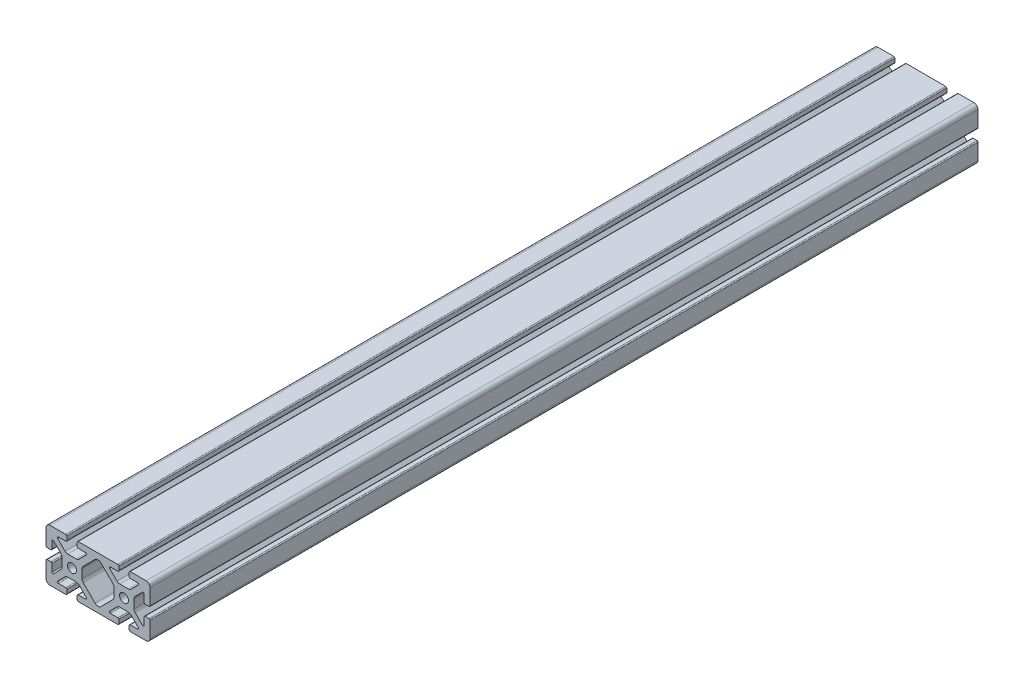
SolidWorks part; units mm, degrees
ref_plane "Front Plane" through (0, 0, 0) normal (0, 0, 1) x (1, 0, 0)
ref_plane "Top Plane" through (0, 0, 0) normal (0, 1, 0) x (1, 0, 0)
ref_plane "Right Plane" through (0, 0, 0) normal (1, 0, 0) x (0, 0, -1)
sketch "Sketch1" plane through (0, 0, 0) normal (0, 0, 1) x (1, 0, 0)
  line L0 (0, 19.939) -> (0, -19.939) construction
  line L1 (-19.939, 0) -> (19.939, 0) construction
  line L2 (-19.939, 16.891) -> (-19.939, 4.7625)
  line L3 (-16.891, 19.939) -> (-4.7625, 19.939)
  line L4 (-4.0005, 19.177) -> (-4.0005, 16.2052)
  line L5 (-4.7625, 15.4432) -> (-10.4246, 15.4432)
  line L6 (-10.9634, 14.1424) -> (-5.395, 8.5741)
  line L7 (-14.1424, 10.9634) -> (-8.5741, 5.395)
  line L8 (-15.4432, 10.4246) -> (-15.4432, 4.7625)
  line L9 (-16.2052, 4.0005) -> (-19.177, 4.0005)
  line L10 (0, 0) -> (-19.939, 19.939) construction
  line L11 (-3.2757, 7.6962) -> (3.2757, 7.6962)
  line L12 (-7.6962, 3.2757) -> (-7.6962, -3.2757)
  line L16 (35.1155, 19.939) -> (4.7625, 19.939)
  line L17 (4.0005, 19.177) -> (4.0005, 16.2052)
  line L18 (4.7625, 15.4432) -> (10.4246, 15.4432)
  line L19 (7.6962, 3.2757) -> (7.6962, -3.2757)
  line L20 (10.9634, 14.1424) -> (5.395, 8.5741)
  line L21 (17.6911, 14.5121) -> (8.5741, 5.395)
  line L22 (-16.2052, -4.0005) -> (-19.177, -4.0005)
  line L23 (-15.4432, -10.4246) -> (-15.4432, -4.7625)
  line L24 (-14.1424, -10.9634) -> (-8.5741, -5.395)
  line L25 (-10.9634, -14.1424) -> (-5.395, -8.5741)
  line L26 (-4.7625, -15.4432) -> (-10.4246, -15.4432)
  line L27 (-4.0005, -19.177) -> (-4.0005, -16.2052)
  line L28 (-16.891, -19.939) -> (-4.7625, -19.939)
  line L29 (-19.939, -16.891) -> (-19.939, -4.7625)
  line L31 (19.939, -19.939) -> (4.7625, -19.939)
  line L32 (4.0005, -19.177) -> (4.0005, -16.2052)
  line L33 (4.7625, -15.4432) -> (10.4246, -15.4432)
  line L34 (10.9634, -14.1424) -> (5.395, -8.5741)
  line L35 (17.6911, -14.5121) -> (8.5741, -5.395)
  line L38 (-3.2757, -7.6962) -> (3.2757, -7.6962)
  line L39 (19.939, 0) -> (19.939, -19.939) construction
  line L40 (43.1537, -7.6962) -> (36.6023, -7.6962)
  line L43 (22.1869, -14.5121) -> (31.3039, -5.395)
  line L44 (28.9146, -14.1424) -> (34.483, -8.5741)
  line L45 (35.1155, -15.4432) -> (29.4534, -15.4432)
  line L46 (35.8775, -19.177) -> (35.8775, -16.2052)
  line L47 (19.939, -19.939) -> (35.1155, -19.939)
  line L48 (59.817, -16.891) -> (59.817, -4.7625)
  line L49 (56.769, -19.939) -> (44.6405, -19.939)
  line L50 (43.8785, -19.177) -> (43.8785, -16.2052)
  line L51 (44.6405, -15.4432) -> (50.3026, -15.4432)
  line L52 (50.8414, -14.1424) -> (45.273, -8.5741)
  line L53 (54.0204, -10.9634) -> (48.4521, -5.395)
  line L54 (55.3212, -10.4246) -> (55.3212, -4.7625)
  line L55 (56.0832, -4.0005) -> (59.055, -4.0005)
  line L56 (22.1869, 14.5121) -> (31.3039, 5.395)
  line L57 (28.9146, 14.1424) -> (34.483, 8.5741)
  line L58 (32.1818, 3.2757) -> (32.1818, -3.2757)
  line L59 (35.1155, 15.4432) -> (29.4534, 15.4432)
  line L60 (35.8775, 19.177) -> (35.8775, 16.2052)
  line L64 (47.5742, 3.2757) -> (47.5742, -3.2757)
  line L65 (43.1537, 7.6962) -> (36.6023, 7.6962)
  line L66 (56.0832, 4.0005) -> (59.055, 4.0005)
  line L67 (55.3212, 10.4246) -> (55.3212, 4.7625)
  line L68 (54.0204, 10.9634) -> (48.4521, 5.395)
  line L69 (50.8414, 14.1424) -> (45.273, 8.5741)
  line L70 (44.6405, 15.4432) -> (50.3026, 15.4432)
  line L71 (43.8785, 19.177) -> (43.8785, 16.2052)
  line L72 (56.769, 19.939) -> (44.6405, 19.939)
  line L73 (59.817, 16.891) -> (59.817, 4.7625)
  circle A0 centre (0, 0) radius 3.4036
  arc A1 (-19.939, 16.891) -> (-16.891, 19.939) centre (-16.891, 16.891) cw
  arc A2 (-14.1424, 10.9634) -> (-15.4432, 10.4246) centre (-14.6812, 10.4246) ccw
  arc A3 (-10.4246, 15.4432) -> (-10.9634, 14.1424) centre (-10.4246, 14.6812) ccw
  arc A4 (-4.7625, 19.939) -> (-4.0005, 19.177) centre (-4.7625, 19.177) cw
  arc A5 (-19.939, 4.7625) -> (-19.177, 4.0005) centre (-19.177, 4.7625) ccw
  arc A6 (-15.4432, 4.7625) -> (-16.2052, 4.0005) centre (-16.2052, 4.7625) cw
  arc A7 (-4.0005, 16.2052) -> (-4.7625, 15.4432) centre (-4.7625, 16.2052) cw
  arc A8 (-3.2757, 7.6962) -> (-5.395, 8.5741) centre (-3.2757, 10.6934) cw
  arc A9 (-7.6962, 3.2757) -> (-8.5741, 5.395) centre (-10.6934, 3.2757) ccw
  arc A10 (22.1869, 14.5121) -> (17.6911, 14.5121) centre (19.939, 12.2642) ccw
  arc A11 (17.6911, -14.5121) -> (22.1869, -14.5121) centre (19.939, -12.2642) ccw
  arc A13 (4.7625, 19.939) -> (4.0005, 19.177) centre (4.7625, 19.177) ccw
  arc A14 (4.0005, 16.2052) -> (4.7625, 15.4432) centre (4.7625, 16.2052) ccw
  arc A15 (3.2757, 7.6962) -> (5.395, 8.5741) centre (3.2757, 10.6934) ccw
  arc A16 (7.6962, 3.2757) -> (8.5741, 5.395) centre (10.6934, 3.2757) cw
  arc A18 (10.4246, 15.4432) -> (10.9634, 14.1424) centre (10.4246, 14.6812) cw
  arc A19 (-7.6962, -3.2757) -> (-8.5741, -5.395) centre (-10.6934, -3.2757) cw
  arc A20 (-3.2757, -7.6962) -> (-5.395, -8.5741) centre (-3.2757, -10.6934) ccw
  arc A21 (-4.0005, -16.2052) -> (-4.7625, -15.4432) centre (-4.7625, -16.2052) ccw
  arc A22 (-15.4432, -4.7625) -> (-16.2052, -4.0005) centre (-16.2052, -4.7625) ccw
  arc A23 (-19.939, -4.7625) -> (-19.177, -4.0005) centre (-19.177, -4.7625) cw
  arc A24 (-4.7625, -19.939) -> (-4.0005, -19.177) centre (-4.7625, -19.177) ccw
  arc A25 (-10.4246, -15.4432) -> (-10.9634, -14.1424) centre (-10.4246, -14.6812) cw
  arc A26 (-14.1424, -10.9634) -> (-15.4432, -10.4246) centre (-14.6812, -10.4246) cw
  arc A27 (-19.939, -16.891) -> (-16.891, -19.939) centre (-16.891, -16.891) ccw
  arc A30 (10.4246, -15.4432) -> (10.9634, -14.1424) centre (10.4246, -14.6812) ccw
  arc A31 (4.7625, -19.939) -> (4.0005, -19.177) centre (4.7625, -19.177) cw
  arc A34 (4.0005, -16.2052) -> (4.7625, -15.4432) centre (4.7625, -16.2052) cw
  arc A35 (3.2757, -7.6962) -> (5.395, -8.5741) centre (3.2757, -10.6934) cw
  arc A36 (7.6962, -3.2757) -> (8.5741, -5.395) centre (10.6934, -3.2757) ccw
  arc A37 (32.1818, -3.2757) -> (31.3039, -5.395) centre (29.1846, -3.2757) cw
  arc A38 (36.6023, -7.6962) -> (34.483, -8.5741) centre (36.6023, -10.6934) ccw
  arc A39 (35.8775, -16.2052) -> (35.1155, -15.4432) centre (35.1155, -16.2052) ccw
  arc A41 (35.1155, -19.939) -> (35.8775, -19.177) centre (35.1155, -19.177) ccw
  arc A42 (29.4534, -15.4432) -> (28.9146, -14.1424) centre (29.4534, -14.6812) cw
  arc A44 (59.817, -16.891) -> (56.769, -19.939) centre (56.769, -16.891) cw
  arc A45 (54.0204, -10.9634) -> (55.3212, -10.4246) centre (54.5592, -10.4246) ccw
  arc A46 (50.3026, -15.4432) -> (50.8414, -14.1424) centre (50.3026, -14.6812) ccw
  arc A47 (44.6405, -19.939) -> (43.8785, -19.177) centre (44.6405, -19.177) cw
  arc A48 (59.817, -4.7625) -> (59.055, -4.0005) centre (59.055, -4.7625) ccw
  arc A49 (55.3212, -4.7625) -> (56.0832, -4.0005) centre (56.0832, -4.7625) cw
  arc A50 (43.8785, -16.2052) -> (44.6405, -15.4432) centre (44.6405, -16.2052) cw
  arc A51 (43.1537, -7.6962) -> (45.273, -8.5741) centre (43.1537, -10.6934) cw
  arc A52 (47.5742, -3.2757) -> (48.4521, -5.395) centre (50.5714, -3.2757) ccw
  arc A53 (29.4534, 15.4432) -> (28.9146, 14.1424) centre (29.4534, 14.6812) ccw
  arc A55 (32.1818, 3.2757) -> (31.3039, 5.395) centre (29.1846, 3.2757) ccw
  arc A56 (36.6023, 7.6962) -> (34.483, 8.5741) centre (36.6023, 10.6934) cw
  arc A57 (35.8775, 16.2052) -> (35.1155, 15.4432) centre (35.1155, 16.2052) cw
  arc A58 (35.1155, 19.939) -> (35.8775, 19.177) centre (35.1155, 19.177) cw
  arc A60 (47.5742, 3.2757) -> (48.4521, 5.395) centre (50.5714, 3.2757) cw
  arc A61 (43.1537, 7.6962) -> (45.273, 8.5741) centre (43.1537, 10.6934) ccw
  arc A62 (43.8785, 16.2052) -> (44.6405, 15.4432) centre (44.6405, 16.2052) ccw
  arc A63 (55.3212, 4.7625) -> (56.0832, 4.0005) centre (56.0832, 4.7625) ccw
  arc A64 (59.817, 4.7625) -> (59.055, 4.0005) centre (59.055, 4.7625) cw
  arc A65 (44.6405, 19.939) -> (43.8785, 19.177) centre (44.6405, 19.177) ccw
  arc A66 (50.3026, 15.4432) -> (50.8414, 14.1424) centre (50.3026, 14.6812) cw
  arc A67 (54.0204, 10.9634) -> (55.3212, 10.4246) centre (54.5592, 10.4246) cw
  arc A68 (59.817, 16.891) -> (56.769, 19.939) centre (56.769, 16.891) ccw
  circle A69 centre (39.878, 0) radius 3.4036
  point P29 (-19.939, 4.0005)
  point P32 (-15.4432, 4.0005)
  point P36 (-4.5172, 7.6962)
  point P68 (0, 7.6962)
  point P219 (39.878, 7.6962)
  dimension "D4" = 6.8072
  dimension "D5" = 3.048
  dimension "D6" = 0.762
  dimension "D9" = 0.762
  dimension "D10" = 0.762
  dimension "D11" = 4.4958
  dimension "D13" = 2.9972
  dimension "D1" = 39.878
  dimension "D2" = 39.878
  dimension "D3" = 12.2428
  dimension "D7" = 8.001
  dimension "D8" = 4.4958
extrude "Extrude1" add sketch "Sketch1" along normal mid plane 635
equation "\"D2@Sketch1\" = \"D1@Sketch1\""
